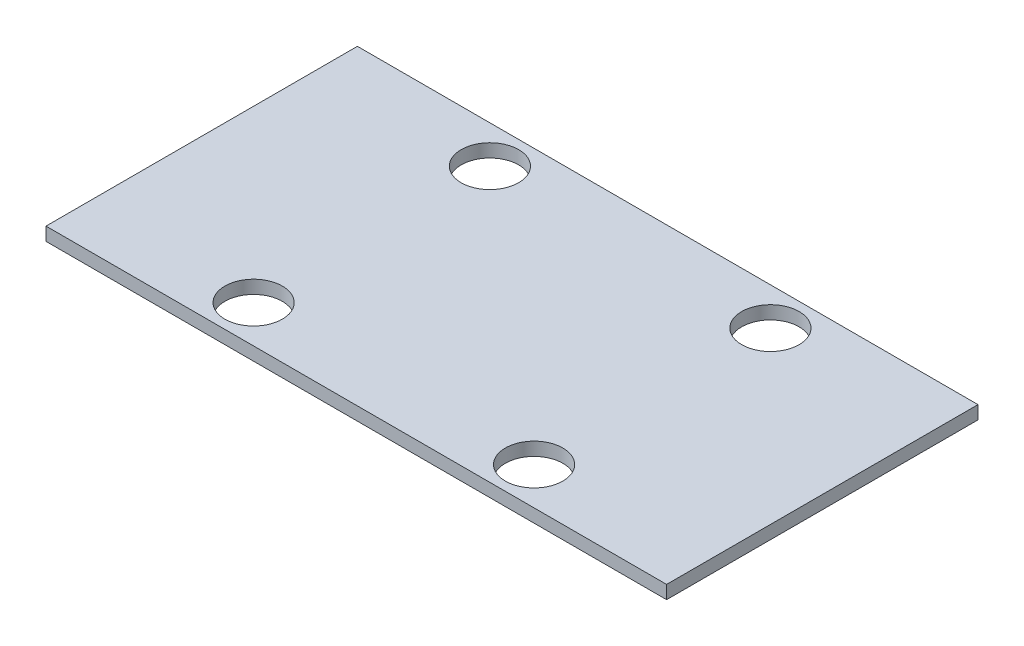
SolidWorks part; units mm, degrees
ref_plane "Front Plane" through (0, 0, 0) normal (0, 0, 1) x (1, 0, 0)
ref_plane "Top Plane" through (0, 0, 0) normal (0, 1, 0) x (1, 0, 0)
ref_plane "Right Plane" through (0, 0, 0) normal (1, 0, 0) x (0, 0, -1)
sketch "Sketch1" plane through (0, 0, 0) normal (0, 1, 0) x (1, 0, 0)
  line L1 (0, 0) -> (71.374, 0)
  line L2 (0, 0) -> (0, 35.814)
  line L3 (0, 35.814) -> (71.374, 35.814)
  line L4 (71.374, 0) -> (71.374, 35.814)
  dimension "D1" = 71.374
  dimension "D2" = 35.814
extrude "Boss-Extrude1" add sketch "Sketch1" along normal blind 1.524
sketch "Sketch2" plane through (0, 1.524, 0) normal (0, 1, 0) x (1, 0, 0)
  line L0 (0, 0) -> (71.374, 0) construction
  line L1 (0, 35.814) -> (0, 0) construction
  line L2 (71.374, 0) -> (71.374, 35.814) construction
  line L3 (71.374, 35.814) -> (0, 35.814) construction
  circle A0 centre (19.558, 4.318) radius 3.302
  circle A1 centre (51.816, 31.496) radius 3.302
  circle A2 centre (19.558, 31.496) radius 3.302
  circle A3 centre (51.816, 4.318) radius 3.302
  dimension "D1" = 4.318
  dimension "D2" = 6.604
  dimension "D4" = 19.558
  dimension "D5" = 4.318
  dimension "D6" = 19.558
  dimension "D7" = 1.016
  dimension "D8" = 19.558
  dimension "D9" = 4.318
  dimension "D3" = 19.558
extrude "Cut-Extrude1" cut sketch "Sketch2" against normal blind 1.524
